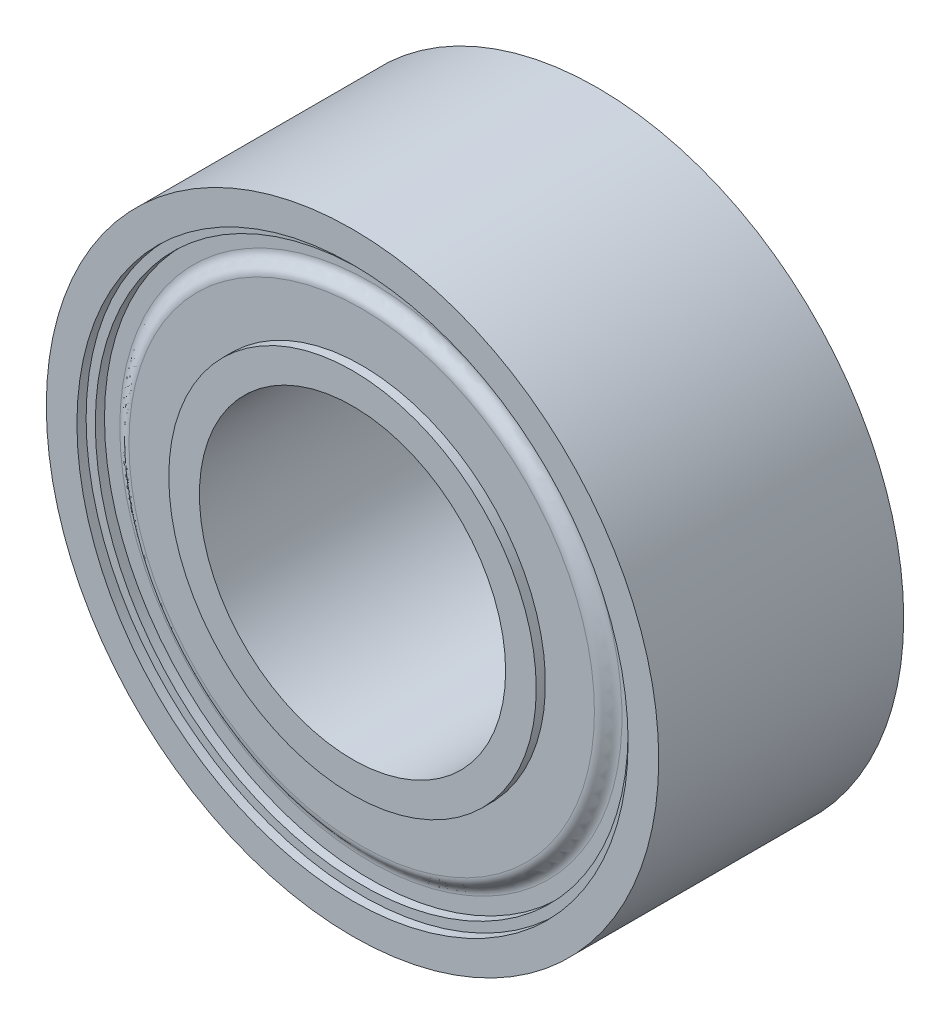
SolidWorks part; units mm, degrees
ref_plane "Спереди" through (0, 0, 0) normal (0, 0, 1) x (1, 0, 0)
ref_plane "Сверху" through (0, 0, 0) normal (0, 1, 0) x (1, 0, 0)
ref_plane "Справа" through (0, 0, 0) normal (1, 0, 0) x (0, 0, -1)
sketch "Эскиз1" plane through (0, 0, 0) normal (0, 0, 1) x (1, 0, 0)
  circle A0 centre (0, 0) radius 5
  circle A1 centre (0, 0) radius 2.5
  circle A2 centre (0, 0) radius 4.5
  circle A3 centre (0, 0) radius 3
extrude "Бобышка-Вытянуть1" add sketch "Эскиз1" along normal mid plane 4 contours A0 A2 | A3 A1
sketch "Эскиз3" plane through (0, 0, 0) normal (0, 1, 0) x (1, 0, 0)
  line L2 (4.35, -1.7) -> (4.1, -1.7)
  line L16 (0, 0) -> (5, 0) construction
  line L17 (5, -2) -> (5, 2) construction
  line L18 (0, 2) -> (0, -2) construction
  line L19 (5, 2) -> (-5, 2) construction
  line L20 (-5, -2) -> (5, -2) construction
  line L22 (4.5, -1.85) -> (4.35, -1.85)
  line L23 (4.35, -1.85) -> (4.35, -1.7)
  line L37 (3.8, 1.85) -> (3.95, 1.85) construction
  line L44 (3.95, 1.85) -> (3.95, 1.7) construction
  line L45 (3.95, 1.7) -> (4.1, 1.7) construction
  line L56 (3.8, -1.85) -> (3.95, -1.85) construction
  line L57 (3.95, -1.85) -> (3.95, -1.7) construction
  line L58 (3.95, -1.7) -> (4.1, -1.7) construction
  line L60 (4.35, 1.85) -> (4.35, 1.7)
  line L61 (4.5, 1.85) -> (4.35, 1.85)
  line L63 (4.35, 1.7) -> (4.1, 1.7)
  line L66 (3, 1.85) -> (3.8, 1.85)
  line L67 (3, 1.85) -> (3, 0)
  line L69 (4.5, 1.85) -> (4.5, 0)
  line L70 (3, -1.85) -> (3.8, -1.85)
  line L71 (4.5, 0) -> (4.5, -1.85)
  line L72 (3, 0) -> (3, -1.85)
  spline S0 degree 3 poles (3.8, -1.85) (3.95, -1.85) (3.95, -1.7) (4.1, -1.7) knots 0 0 0 0 1 1 1 1
  spline S1 degree 3 poles (3.8, 1.85) (3.95, 1.85) (3.95, 1.7) (4.1, 1.7) knots 0 0 0 0 1 1 1 1
revolve "Повернуть1" add sketch "Эскиз3" angle 360 about L18
